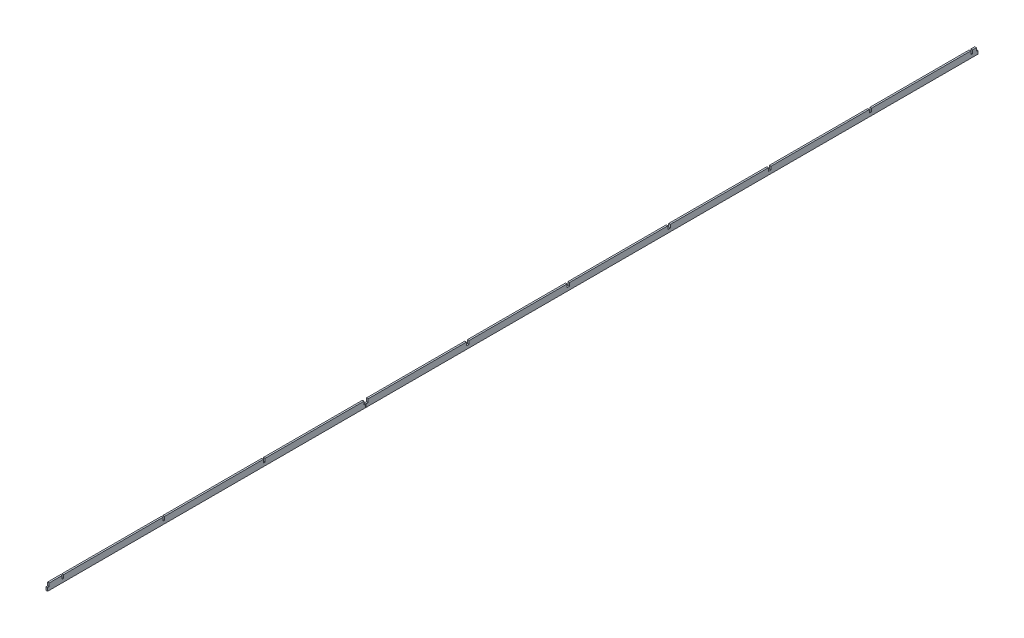
SolidWorks part; units mm, degrees
material "轻木"
ref_plane "前视基准面" through (0, 0, 0) normal (0, 0, 1) x (1, 0, 0)
ref_plane "上视基准面" through (0, 0, 0) normal (0, 1, 0) x (1, 0, 0)
ref_plane "右视基准面" through (0, 0, 0) normal (1, 0, 0) x (0, 0, -1)
other "Configuration Table"
sketch "草图1" plane through (0, 0, -55.99) normal (0, 0, 1) x (1, 0, 0)
  line L1 (86.0376, -3.0621) -> (84.0376, -3.0621)
  line L2 (86.0376, -3.0621) -> (86.0376, 4.9379)
  line L3 (86.0376, 4.9379) -> (84.0376, 4.9379)
  line L4 (84.0376, -3.0621) -> (84.0376, 4.9379)
  dimension "D1" = 8
  dimension "D2" = 2
extrude "凸台-拉伸1" add sketch "草图1" along normal blind 1155
sketch "草图2" plane through (86.0376, 0, 0) normal (1, 0, 0) x (0, 0, -1)
  line L0 (-1099.01, -3.0621) -> (55.99, -3.0621) construction
  line L1 (55.99, 4.9379) -> (53.99, 4.9379)
  line L2 (55.99, 4.9379) -> (55.99, 0.9379)
  line L3 (55.99, 0.9379) -> (53.99, 0.9379)
  line L4 (53.99, 4.9379) -> (53.99, 0.9379)
  line L5 (53.99, -2.2615) -> (53.99, -3.0621) construction
  line L6 (-1099.01, 4.9379) -> (55.99, 4.9379) construction
  line L7 (55.99, -1.0553) -> (55.99, 24.1798) construction
  line L8 (48.99, -1.0553) -> (48.99, 25.6795) construction
  line L13 (48.99, 4.9379) -> (45.99, 4.9379)
  line L38 (48.99, 4.9379) -> (48.99, 0.8967)
  line L41 (-704.11, 0.8967) -> (-703.91, 0.8967)
  line L55 (-76.01, 4.9379) -> (-79.01, 4.9379)
  line L56 (-704.11, 0.8967) -> (-704.11, -3.0621)
  line L61 (48.99, 0.8967) -> (45.99, 0.8967)
  line L62 (-76.01, 4.9379) -> (-76.01, 0.8967)
  line L63 (-76.01, 0.8967) -> (-79.01, 0.8967)
  line L64 (45.99, 4.9379) -> (45.99, 0.8967)
  line L65 (-79.01, 4.9379) -> (-79.01, 0.8967)
  line L66 (48.99, 4.9379) -> (-76.01, 4.9379) construction
  line L67 (-201.01, 4.9379) -> (-204.01, 4.9379)
  line L68 (-201.01, 4.9379) -> (-201.01, 0.8967)
  line L69 (-201.01, 0.8967) -> (-204.01, 0.8967)
  line L70 (-204.01, 4.9379) -> (-204.01, 0.8967)
  line L71 (-326.01, 4.9379) -> (-329.01, 4.9379)
  line L72 (-326.01, 4.9379) -> (-326.01, 0.8967)
  line L73 (-326.01, 0.8967) -> (-329.01, 0.8967)
  line L74 (-329.01, 4.9379) -> (-329.01, 0.8967)
  line L75 (-451.01, 4.9379) -> (-454.01, 4.9379)
  line L76 (-451.01, 4.9379) -> (-451.01, 0.8967)
  line L77 (-451.01, 0.8967) -> (-454.01, 0.8967)
  line L78 (-454.01, 4.9379) -> (-454.01, 0.8967)
  line L79 (-576.01, 4.9379) -> (-579.01, 4.9379)
  line L80 (-576.01, 4.9379) -> (-576.01, 0.8967)
  line L81 (-576.01, 0.8967) -> (-579.01, 0.8967)
  line L82 (-579.01, 4.9379) -> (-579.01, 0.8967)
  line L83 (-701.01, 4.9379) -> (-704.01, 4.9379)
  line L84 (-701.01, 4.9379) -> (-701.01, 0.8967)
  line L85 (-701.01, 0.8967) -> (-704.01, 0.8967)
  line L86 (-704.01, 4.9379) -> (-704.01, 0.8967)
  line L87 (-829.01, 4.9379) -> (-829.01, 0.8967)
  line L88 (-704.01, 4.9379) -> (-706.01, 4.9379)
  line L89 (-704.01, 4.9379) -> (-704.01, 0.8967)
  line L90 (-704.01, 0.8967) -> (-706.01, 0.8967)
  line L91 (-706.01, 4.9379) -> (-706.01, 0.8967)
  line L92 (-829.01, 4.9379) -> (-831.01, 4.9379)
  line L93 (-829.01, 4.9379) -> (-829.01, 0.8967)
  line L94 (-829.01, 0.8967) -> (-831.01, 0.8967)
  line L95 (-831.01, 4.9379) -> (-831.01, 0.8967)
  line L96 (-954.01, 4.9379) -> (-954.01, 0.8967)
  line L97 (-954.01, 4.9379) -> (-956.01, 4.9379)
  line L98 (-954.01, 4.9379) -> (-954.01, 0.8967)
  line L99 (-954.01, 0.8967) -> (-956.01, 0.8967)
  line L100 (-956.01, 4.9379) -> (-956.01, 0.8967)
  line L101 (-1079.01, 4.9379) -> (-1079.01, 0.8967)
  line L102 (-1079.01, 4.9379) -> (-1081.01, 4.9379)
  line L103 (-1079.01, 4.9379) -> (-1079.01, 0.8967)
  line L104 (-1079.01, 0.8967) -> (-1081.01, 0.8967)
  line L105 (-1081.01, 4.9379) -> (-1081.01, 0.8967)
  line L106 (-704.01, 4.9379) -> (-829.01, 4.9379) construction
  line L107 (-704.11, -3.0621) -> (-703.91, -3.0621)
  line L108 (-1097.01, 3.5406) -> (-1097.01, 0.4906) construction
  line L109 (-1099.01, -3.0621) -> (-1099.01, 4.9379) construction
  line L110 (-1097.01, 0.8967) -> (-1099.01, 0.8967)
  line L111 (-1097.01, 0.8967) -> (-1097.01, 4.9379)
  line L112 (-1097.01, 4.9379) -> (-1099.01, 4.9379)
  line L113 (-1099.01, 0.8967) -> (-1099.01, 4.9379)
  line L114 (-703.91, 0.8967) -> (-703.91, -3.0621)
  line L115 (-704.01, 25.6795) -> (-704.01, -1.0553) construction
  line M5 (55.99, -3.0621) -> (55.99, 4.9379)
  line M6 (55.99, 4.9379) -> (-1099.01, 4.9379)
  line M7 (-1099.01, 4.9379) -> (-1099.01, -3.0621)
  line M8 (-1099.01, -3.0621) -> (55.99, -3.0621)
  dimension "D1" = 125
  dimension "D2" = 7
  dimension "D4" = 4
  dimension "D5" = 4
  dimension "D3" = 125
  dimension "D6" = 0.2
  dimension "D7" = 0.1
  dimension "D8" = 3
extrude "切除-拉伸1" cut sketch "草图2" against normal through all contours L110 L111 M6 M7 | L105 L104 L101 M6 | L100 L99 L96 M6 | L95 L94 L87 M6 | L91 L90 L86 M6 | L86 L85 L84 M6 | L82 L81 L80 M6 | L78 L77 L76 M6 | L74 L73 L72 M6 | L70 L69 L68 M6 | L65 L63 L62 M6 | L64 L61 L38 M6 | L4 L3 M6 M5 | L114 L41 L56 M8
sketch "草图3" plane through (86.0376, 0, 0) normal (1, 0, 0) x (0, 0, -1)
  line L0 (-76.01, 4.9379) -> (45.99, 4.9379) construction
  line L1 (45.99, 0.8967) -> (46.99, 0.8967)
  line L2 (45.99, 0.8967) -> (45.99, 4.9379)
  line L3 (45.99, 4.9379) -> (46.99, 4.9379)
  line L4 (46.99, 0.8967) -> (46.99, 4.9379)
  dimension "D2" = 1
extrude "凸台-拉伸2" add sketch "草图3" against normal blind 2
